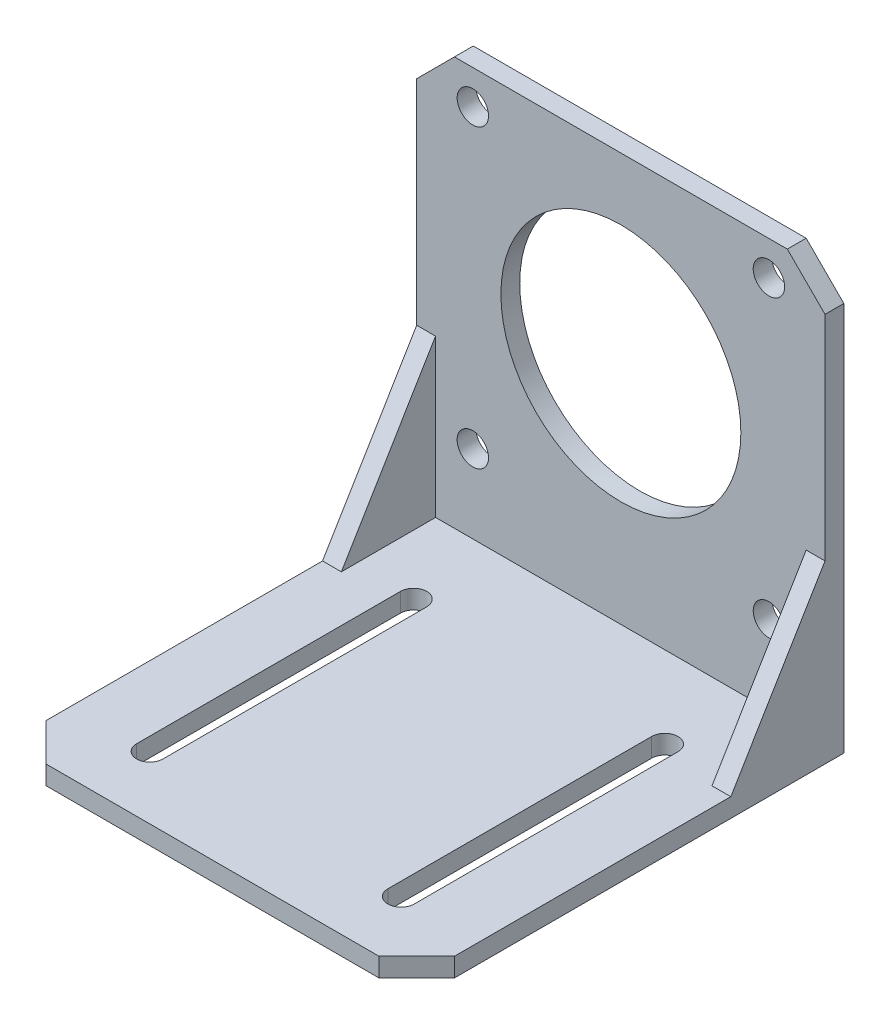
SolidWorks part; units mm, degrees
ref_plane "Front Plane" through (0, 0, 0) normal (0, 0, 1) x (1, 0, 0)
ref_plane "Top Plane" through (0, 0, 0) normal (0, 1, 0) x (1, 0, 0)
ref_plane "Right Plane" through (0, 0, 0) normal (1, 0, 0) x (0, 0, -1)
sketch "Sketch1" plane through (0, 0, 0) normal (0, 1, 0) x (1, 0, 0)
  line L0 (65, 0) -> (52.5, 0)
  line L1 (0, 0) -> (65, 0)
  line L2 (0, 0) -> (0, 65)
  line L3 (0, 65) -> (65, 65)
  line L4 (65, 0) -> (65, 65)
  line L5 (52.5, 0) -> (52.5, 10)
  line L6 (52.5, 10) -> (12.5, 10)
  line L7 (12.5, 10) -> (12.5, 52)
  line L8 (12.5, 52) -> (52.5, 52)
  line L9 (0, 0) -> (0, 6)
  line L10 (0, 6) -> (6, 0)
  line L11 (65, 0) -> (59, 0)
  line L12 (59, 0) -> (65, 6)
  line L13 (10.4, 52) -> (10.4, 10)
  line L14 (14.6241, 52) -> (14.6, 10)
  line L15 (50.4, 52) -> (50.4, 10)
  line L16 (54.6, 52) -> (54.6, 10)
  circle A0 centre (12.5, 52) radius 2.1
  circle A1 centre (52.5, 52) radius 2.1
  circle A2 centre (12.5, 10) radius 2.1
  circle A3 centre (52.5, 10) radius 2.1
  dimension "D1" = 65
  dimension "D2" = 65
extrude "Boss-Extrude1" add sketch "Sketch1" along normal blind 3
sketch "Sketch2" plane through (0, 3, 0) normal (0, 1, 0) x (1, 0, 0)
  line L0 (65, 6) -> (65, 65) construction
  line L1 (0, 65) -> (65, 65)
  line L2 (0, 65) -> (0, 62)
  line L3 (0, 62) -> (65, 62)
  line L4 (65, 65) -> (65, 62)
  dimension "D1" = 3
extrude "Boss-Extrude2" add sketch "Sketch2" along normal blind 65
sketch "Sketch3" plane through (0, 0, -62) normal (0, 0, 1) x (1, 0, 0)
  line L0 (0, 68) -> (6, 68)
  line L1 (0, 68) -> (65, 68) construction
  line L2 (6, 68) -> (0, 62)
  line L3 (0, 68) -> (0, 3) construction
  line L4 (65, 68) -> (59, 68)
  line L5 (59, 68) -> (65, 62)
  line L6 (65, 68) -> (65, 3) construction
  line L7 (0, 68) -> (0, 39)
  line L8 (32.5, 68) -> (32.5, 39)
  line L9 (0, 60.0743) -> (8.93, 60.0743)
  line L10 (32.5, 58.1) -> (32.5, 62.57)
  line L11 (32.5, 62.57) -> (8.93, 62.57)
  line L12 (32.5, 62.57) -> (56.07, 62.57)
  line L13 (56.07, 62.57) -> (56.07, 15.43)
  line L14 (56.07, 15.43) -> (8.93, 15.43)
  circle A0 centre (32.5, 39) radius 19.1
  circle A1 centre (56.07, 62.57) radius 2.5
  circle A2 centre (8.93, 62.57) radius 2.5
  circle A3 centre (56.07, 15.43) radius 2.5
  circle A4 centre (8.93, 15.43) radius 2.5
extrude "Cut-Extrude1" cut sketch "Sketch3" against normal up to next
sketch "Sketch4" plane through (0, 0, -65) normal (0, 0, -1) x (-1, 0, 0)
  line L0 (-65, 62) -> (-59, 68)
  line L1 (-59, 68) -> (-6, 68)
  line L2 (-6, 68) -> (0, 62)
  line L3 (0, 62) -> (0, 0)
  line L4 (0, 0) -> (-65, 0)
  line L5 (-65, 0) -> (-65, 62)
  circle A0 centre (-32.5, 39) radius 19.1
  circle A1 centre (-56.07, 62.57) radius 2.5
  circle A2 centre (-8.93, 62.57) radius 2.5
extrude "Boss-Extrude3" add sketch "Sketch4" along normal blind 3
sketch "Sketch5" plane through (0, 0, -62) normal (0, 0, 1) x (1, 0, 0)
  line L1 (0, 69.4839) -> (65, 69.4839)
  line L2 (0, 69.4839) -> (0, 3)
  line L3 (0, 3) -> (65, 3)
  line L4 (65, 69.4839) -> (65, 3)
extrude "Cut-Extrude2" cut sketch "Sketch5" against normal blind 3
sketch "Sketch6" plane through (0, 0, -68) normal (0, 0, -1) x (-1, 0, 0)
  line L0 (-56.07, 62.57) -> (-56.07, 15.43)
  line L1 (-56.07, 15.43) -> (-8.93, 15.43)
  circle A0 centre (-56.07, 15.43) radius 2.5
  circle A1 centre (-8.93, 15.43) radius 2.5
extrude "Cut-Extrude3" cut sketch "Sketch6" against normal blind 3
sketch "Sketch7" plane through (0, 0, 0) normal (-1, 0, 0) x (0, 0, 1)
  line L0 (-65, 3) -> (-50, 3)
  line L1 (-6, 3) -> (-65, 3) construction
  line L2 (-65, 3) -> (-65, 28)
  line L3 (-65, 62) -> (-65, 3) construction
  line L4 (-65, 28) -> (-50, 3)
extrude "Boss-Extrude5" add sketch "Sketch7" against normal blind 3
sketch "Sketch8" plane through (65, 0, 0) normal (1, 0, 0) x (0, 0, -1)
  line L0 (65, 3) -> (50, 3)
  line L1 (50, 3) -> (65, 28)
  line L2 (65, 28) -> (65, 3)
extrude "Boss-Extrude6" add sketch "Sketch8" against normal blind 3
